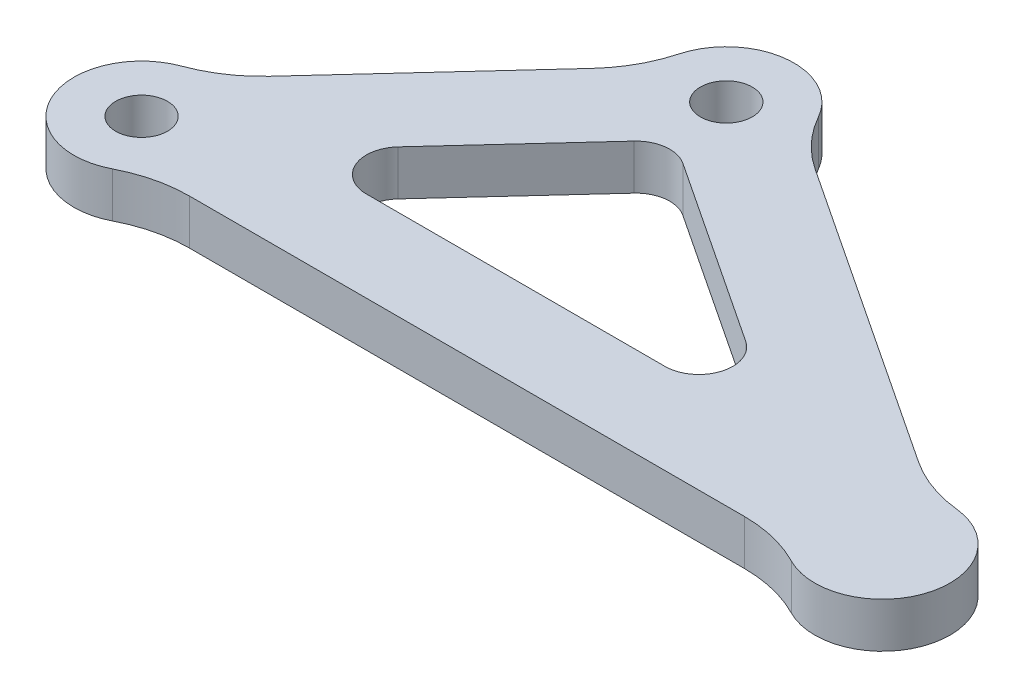
SolidWorks part; units mm, degrees
ref_plane "Спереди" through (0, 0, 0) normal (0, 0, 1) x (1, 0, 0)
ref_plane "Сверху" through (0, 0, 0) normal (0, 1, 0) x (1, 0, 0)
ref_plane "Справа" through (0, 0, 0) normal (1, 0, 0) x (0, 0, -1)
sketch "Эскиз1" plane through (0, 0, 0) normal (0, 1, 0) x (1, 0, 0)
  line L0 (0, 0) -> (32.85, 0) construction
  line L2 (0, 0) -> (12.4139, 13.5136) construction
  line L4 (12.4139, 13.5136) -> (32.85, 0) construction
  line L5 (9.4283, 13.2199) -> (0.0398, 2.9997)
  line L9 (4.553, 2) -> (12.7332, 10.9048)
  line L10 (2.2361, -2) -> (30.6139, -2)
  line L11 (15.3822, 13.9485) -> (32.088, 2.9016)
  line L12 (48.8722, -2) -> (6.6986, 8.6954) construction
  line L13 (12.7332, 10.9048) -> (26.1995, 2)
  line L14 (43.7931, -4.8385) -> (5.7153, 4.8182) construction
  line L15 (32.85, 0) -> (6.207, 6.7568) construction
  line L16 (0, -2) -> (48.8722, -2) construction
  line L17 (4.553, 2) -> (26.1995, 2)
  line L18 (13.5171, 15.1818) -> (43.7931, -4.8385) construction
  circle A0 centre (0, 0) radius 1.15
  circle A4 centre (12.4139, 13.5136) radius 1.15
  arc A5 (15.3822, 13.9485) -> (9.4283, 13.2199) centre (12.4139, 13.5136) ccw
  arc A6 (0.0398, 2.9997) -> (2.2361, -2) centre (0, 0) ccw
  arc A15 (30.6139, -2) -> (32.088, 2.9016) centre (32.85, 0) ccw
  point P16 (6.207, 6.7568)
  dimension "D4" = 2.3
  dimension "D5" = 2
  dimension "D6" = 2
  dimension "D7" = 18.35
  dimension "D8" = 2.3
  dimension "D9" = 6
  dimension "D12" = 3
  dimension "D3" = 6
  dimension "D1" = 32.85
  dimension "D2" = 24.5
  dimension "D10" = 2
  dimension "D11" = 2
extrude "Бобышка-Вытянуть1" add sketch "Эскиз1" along normal blind 2
fillet "Скругление1" radius 6 6 edges at (9.4283, 1, -13.2199) (0.0398, 1, -2.9997) (32.088, 1, -2.9016) (30.6139, 1, 2) (2.2361, 1, 2) (15.3822, 1, -13.9485)
fillet "Скругление2" radius 1.5 3 edges at (4.553, 1, -2) (12.7332, 1, -10.9048) (26.1995, 1, -2)
